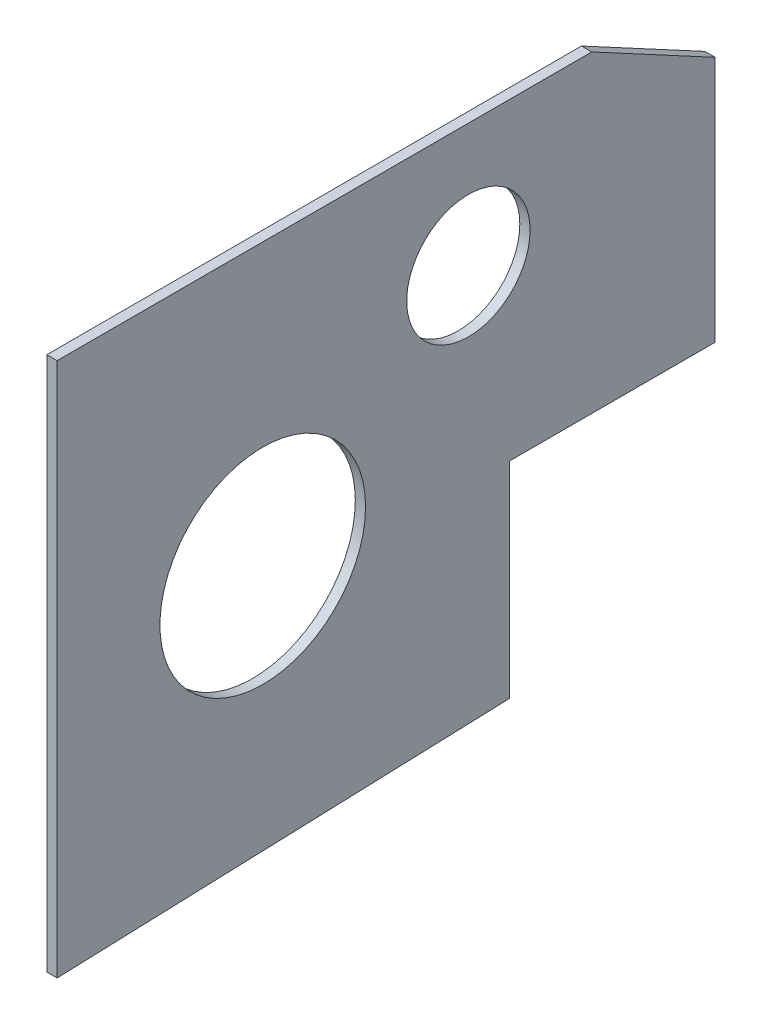
SolidWorks part; units mm, degrees
ref_plane "Front Plane" through (0, 0, 0) normal (0, 0, 1) x (1, 0, 0)
ref_plane "Top Plane" through (0, 0, 0) normal (0, 1, 0) x (1, 0, 0)
ref_plane "Right Plane" through (0, 0, 0) normal (1, 0, 0) x (0, 0, -1)
sketch "Sketch2" plane through (0, 0, 0) normal (1, 0, 0) x (0, 0, -1)
  line L0 (-337.9428, 83.7775) -> (-172.8428, 83.7775)
  line L1 (-172.8428, 83.7775) -> (-134.7428, 63.2875)
  line L2 (-134.7428, 63.2875) -> (-134.7428, -12.9125)
  line L3 (-134.7428, -12.9125) -> (-198.2428, -12.9125)
  line L4 (-198.2428, -12.9125) -> (-198.2428, -76.4125)
  line L5 (-198.2428, -76.4125) -> (-337.9428, -81.3225)
  line L6 (-337.9428, -81.3225) -> (-337.9428, 83.7775)
  dimension "D1" = 165.1
  dimension "D2" = 63.5
  dimension "D3" = 139.7
  dimension "D4" = 165.1
  dimension "D5" = 63.5
  dimension "D6" = 203.2
extrude "Boss-Extrude1" add sketch "Sketch2" along normal blind 3.175 contours L6 L0 L1 L2 L3 L4 L5
sketch "Sketch3" plane through (3.175, 0, 0) normal (1, 0, 0) x (0, 0, -1)
  line L0 (-198.2428, -76.4125) -> (-337.9428, -81.3225) construction
  line L1 (-337.9428, -81.3225) -> (-337.9428, 83.7775) construction
  line L2 (-337.9428, 83.7775) -> (-172.8428, 83.7775) construction
  circle A0 centre (-274.4428, -2.8436) radius 31.75
  circle A1 centre (-210.9428, 45.6775) radius 19.05
  point P10 (0, 0)
  dimension "D1" = 63.5
  dimension "D3" = 63.5
  dimension "D4" = 38.1
  dimension "D6" = 38.1
  dimension "D2" = 76.2
  dimension "D5" = 127
extrude "Cut-Extrude3" cut sketch "Sketch3" against normal through all contours A1 | A0
